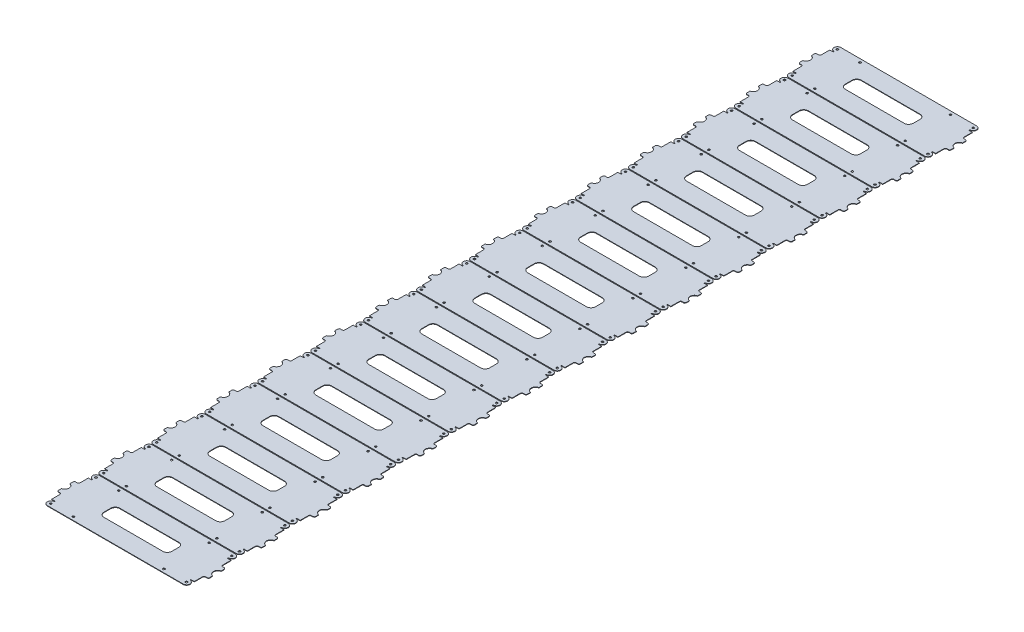
SolidWorks part; units mm, degrees
ref_plane "Front Plane" through (0, 0, 0) normal (0, 0, 1) x (1, 0, 0)
ref_plane "Top Plane" through (0, 0, 0) normal (0, 1, 0) x (1, 0, 0)
ref_plane "Right Plane" through (0, 0, 0) normal (1, 0, 0) x (0, 0, -1)
sketch "Sketch1" plane through (0, 0, 0) normal (0, 1, 0) x (1, 0, 0)
  line L1 (-157.5, 42.5) -> (157.5, 42.5) construction
  line L2 (-157.5, 42.5) -> (-157.5, -42.5) construction
  line L3 (-157.5, -42.5) -> (157.5, -42.5) construction
  line L4 (157.5, 42.5) -> (157.5, -42.5) construction
  line L5 (-157.5, 42.5) -> (157.5, -42.5) construction
  line L6 (-157.5, -42.5) -> (157.5, 42.5) construction
  line L19 (154.5, -40.5) -> (-154.5, -40.5) construction
  line L20 (154.5, -40.5) -> (154.5, 40.5) construction
  line L21 (154.5, 40.5) -> (-154.5, 40.5) construction
  line L22 (-154.5, -40.5) -> (-154.5, 40.5) construction
  line L23 (154.5, -40.5) -> (-154.5, 40.5) construction
  line L24 (154.5, 40.5) -> (-154.5, -40.5) construction
  line L25 (150, 57.5) -> (-150, 57.5)
  line L28 (-167.025, 19) -> (-167.025, 9.3127)
  line L31 (-150, -57.5) -> (150, -57.5)
  line L34 (167.025, -19) -> (167.025, -9.3127)
  line L36 (-157.5, 0) -> (-167.025, 0) construction
  line L37 (157.5, 0) -> (167.025, 0) construction
  line L38 (-157.5, 40.5) -> (-154.5, 40.5) construction
  line L43 (-167.025, 0) -> (-169.025, 0) construction
  line L44 (-167.025, -9.3127) -> (-167.025, -19)
  line L45 (-154.5, 40.5) -> (-154.5, 42.5) construction
  line L46 (-154.5, -42.5) -> (-154.5, -40.5) construction
  line L47 (-154.5, -40.5) -> (-157.5, -40.5) construction
  line L48 (154.5, -42.5) -> (154.5, -40.5) construction
  line L49 (154.5, -40.5) -> (157.5, -40.5) construction
  line L50 (154.5, 40.5) -> (154.5, 42.5) construction
  line L51 (157.5, 40.5) -> (154.5, 40.5) construction
  line L54 (-167.025, 19) -> (-157.5, 19)
  line L55 (-157.5, 19) -> (-157.5, 40.5)
  line L56 (-167.025, -19) -> (-157.5, -19)
  line L57 (-157.5, -19) -> (-157.5, -40.5)
  line L62 (167.025, -19) -> (157.5, -19)
  line L63 (157.5, -19) -> (157.5, -40.5)
  line L64 (167.025, 19) -> (157.5, 19)
  line L65 (157.5, 19) -> (157.5, 40.5)
  line L68 (0, 50) -> (0, 0) construction
  line L69 (150, 0) -> (0, 0) construction
  line L70 (-167.025, 9.3127) -> (-167.025, 0) construction
  line L71 (-150, 50) -> (150, 50) construction
  line L72 (-150, 50) -> (-150, -50) construction
  line L73 (-150, -50) -> (150, -50) construction
  line L74 (150, 50) -> (150, -50) construction
  line L75 (-167.025, 0) -> (-167.025, -9.3127) construction
  line L76 (169.025, 0) -> (167.025, 0) construction
  line L77 (167.025, 9.3127) -> (167.025, 19)
  line L78 (167.025, 9.3127) -> (167.025, 0) construction
  line L79 (167.025, 0) -> (167.025, -9.3127) construction
  line L80 (-150, 57.5) -> (-150, 42.5) construction
  line L81 (150, 57.5) -> (150, 42.5) construction
  line L82 (-150, -57.5) -> (-150, -42.5) construction
  line L83 (150, -57.5) -> (150, -42.5) construction
  line L84 (-157.5, -40.5) -> (-150, -40.5)
  line L85 (-150, -40.5) -> (-150, -42.5)
  line L86 (-157.5, 50) -> (-157.5, -50) construction
  line L87 (157.5, 50) -> (157.5, -50) construction
  line L88 (-157.5, -50) -> (-157.5, -40.5) construction
  line L89 (-159.5, 0) -> (0, 0) construction
  line L90 (-150, 42.5) -> (-150, 40.5)
  line L91 (-140, 25) -> (140, 25) construction
  line L92 (-140, 25) -> (-140, -25) construction
  line L93 (-140, -25) -> (140, -25) construction
  line L94 (140, 25) -> (140, -25) construction
  line L95 (-140, 25) -> (140, -25) construction
  line L96 (-140, -25) -> (140, 25) construction
  line L97 (-75, 17.5) -> (75, 17.5)
  line L98 (-75, 17.5) -> (-75, -17.5)
  line L99 (-75, -17.5) -> (75, -17.5)
  line L100 (75, 17.5) -> (75, -17.5)
  line L101 (-75, 17.5) -> (75, -17.5) construction
  line L102 (-75, -17.5) -> (75, 17.5) construction
  line L103 (-150, 40.5) -> (-157.5, 40.5)
  line L105 (150, 42.5) -> (150, 40.5)
  line L106 (150, 40.5) -> (157.5, 40.5)
  line L108 (150, -42.5) -> (150, -40.5)
  line L109 (150, -40.5) -> (157.5, -40.5)
  circle A8 centre (-150, 50) radius 2.2
  circle A9 centre (150, 50) radius 2.2
  circle A10 centre (150, -50) radius 2.2
  circle A11 centre (-150, -50) radius 2.2
  circle A12 centre (-169.025, 0) radius 9.525 construction
  arc A13 (-167.025, -9.3127) -> (-167.025, 9.3127) centre (-169.025, 0) ccw
  circle A14 centre (169.025, 0) radius 9.525 construction
  arc A15 (167.025, 9.3127) -> (167.025, -9.3127) centre (169.025, 0) ccw
  arc A16 (150, 42.5) -> (150, 57.5) centre (150, 50) ccw
  arc A17 (-150, 57.5) -> (-150, 42.5) centre (-150, 50) ccw
  arc A18 (-150, -42.5) -> (-150, -57.5) centre (-150, -50) ccw
  arc A19 (150, -42.5) -> (150, -57.5) centre (150, -50) cw
  circle A24 centre (-140, 25) radius 2 construction
  circle A25 centre (-140, -25) radius 2 construction
  circle A26 centre (140, -25) radius 2 construction
  circle A27 centre (140, 25) radius 2 construction
  circle A28 centre (-100, 50) radius 2.2
  circle A29 centre (100, 50) radius 2.2
  circle A30 centre (100, -50) radius 2.2
  circle A31 centre (-100, -50) radius 2.2
  point P0 (0, 0)
  point P5 (0, 0)
  point P31 (0, 0)
  point P45 (-159.5, 0)
  point P50 (159.5, 0)
  dimension "D5" = 38
  dimension "D9" = 19.05
  dimension "D11" = 10
  dimension "D16" = 2
  dimension "D13" = 4.4
  dimension "D18" = 19.05
  dimension "D6" = 50
  dimension "D14" = 25
  dimension "D3" = 4
  dimension "D19" = 50
  dimension "D23" = 4
  dimension "D2" = 300
  dimension "D4" = 3
  dimension "D7" = 38
  dimension "D8" = 2
  dimension "D10" = 15
  dimension "D12" = 2
  dimension "D15" = 75
  dimension "D17" = 2
  dimension "D20" = 50
  dimension "D21" = 50
  dimension "D22" = 50
  dimension "D24" = 81
  dimension "D25" = 2
  dimension "D26" = 200
extrude "Boss-Extrude1" add sketch "Sketch1" along normal blind 1
fillet "Fillet1" radius 10 4 edges at (75, 0.5, 17.5) (75, 0.5, -17.5) (-75, 0.5, -17.5) (-75, 0.5, 17.5)
fillet "Fillet2" radius 3 8 edges at (167.025, 0.5, -19) (157.5, 0.5, -19) (157.5, 0.5, 19) (167.025, 0.5, 19) (-157.5, 0.5, -19) (-167.025, 0.5, -19) (-157.5, 0.5, 19) (-167.025, 0.5, 19)
pattern_linear "LPattern1" count 15 spacing 117 along (0, 0, -1) of bodies 101
